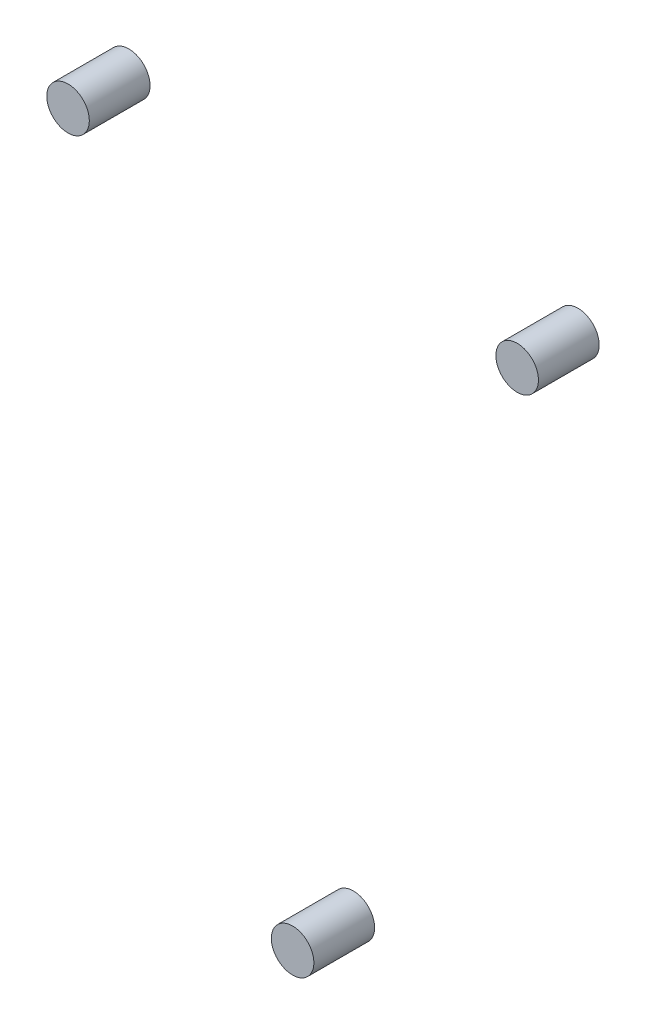
SolidWorks part; units mm, degrees
ref_plane "Front Plane" through (0, 0, 0) normal (0, 0, 1) x (1, 0, 0)
ref_plane "Top Plane" through (0, 0, 0) normal (0, 1, 0) x (1, 0, 0)
ref_plane "Right Plane" through (0, 0, 0) normal (1, 0, 0) x (0, 0, -1)
sketch "Sketch1" plane through (0, 0, 0) normal (0, 0, 1) x (1, 0, 0)
  line L0 (0, 57.5) -> (0, 0) construction
  line L1 (0, 0) -> (-36.9603, 44.0476) construction
  circle A1 centre (0, -57.5) radius 3.5
  circle A2 centre (0, 0) radius 57.5 construction
  circle A3 centre (-36.9603, 44.0476) radius 3.5
  circle A4 centre (36.9603, 44.0476) radius 3.5
  dimension "D1" = 7
  dimension "D2" = 115
  dimension "D3" = 40
extrude "Boss-Extrude1" add sketch "Sketch1" along normal blind 10
